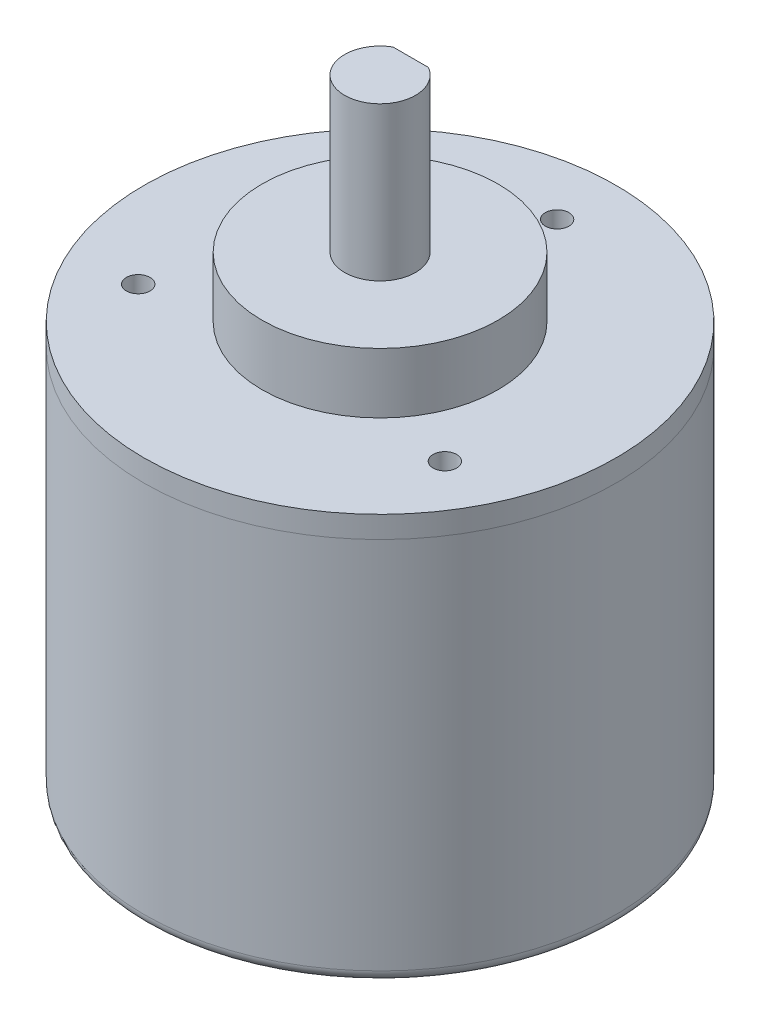
SolidWorks part; units mm, degrees
ref_plane "Ön Düzlem" through (0, 0, 0) normal (0, 0, 1) x (1, 0, 0)
ref_plane "Üst Düzlem" through (0, 0, 0) normal (0, 1, 0) x (1, 0, 0)
ref_plane "Sağ Düzlem" through (0, 0, 0) normal (1, 0, 0) x (0, 0, -1)
sketch "Çizim1" plane through (0, 0, 0) normal (0, 1, 0) x (1, 0, 0)
  circle A0 centre (0, 0) radius 20
  dimension "D1" = 40
extrude "Yükseklik-Ekstrüzyon1" add sketch "Çizim1" along normal blind 32.65
sketch "Çizim2" plane through (0, 32.65, 0) normal (0, 1, 0) x (1, 0, 0)
  circle A0 centre (0, 0) radius 20
extrude "Yükseklik-Ekstrüzyon2" add sketch "Çizim2" along normal blind 1.85 separate body
sketch "Çizim3" plane through (0, 34.5, 0) normal (0, 1, 0) x (1, 0, 0)
  circle A0 centre (0, 0) radius 10
  dimension "D1" = 20
extrude "Yükseklik-Ekstrüzyon3" add sketch "Çizim3" along normal blind 5.1
sketch "Çizim4" plane through (0, 34.5, 0) normal (0, 1, 0) x (1, 0, 0)
  circle A0 centre (0, 0) radius 15 construction
  circle A1 centre (0, 15) radius 1
  circle A2 centre (0, 0) radius 20 construction
  circle A3 centre (12.9904, -7.5) radius 1
  circle A4 centre (-12.9904, -7.5) radius 1
  point P13 (0, 0)
  dimension "D1" = 5
  dimension "D2" = 2
  dimension "D3" = 3
extrude "Kes-Ekstrüzyon1" cut sketch "Çizim4" against normal blind 10
fillet "Radyus1" radius 1 1 edges at (0, 0, 20)
sketch "Çizim5" plane through (0, 39.6, 0) normal (0, 1, 0) x (1, 0, 0)
  line L0 (-1.5, 2.5981) -> (1.5, 2.5981)
  arc A0 (-1.5, 2.5981) -> (1.5, 2.5981) centre (0, 0) ccw
  dimension "D1" = 6
  dimension "D2" = 3
extrude "Yükseklik-Ekstrüzyon4" add sketch "Çizim5" along normal blind 13
